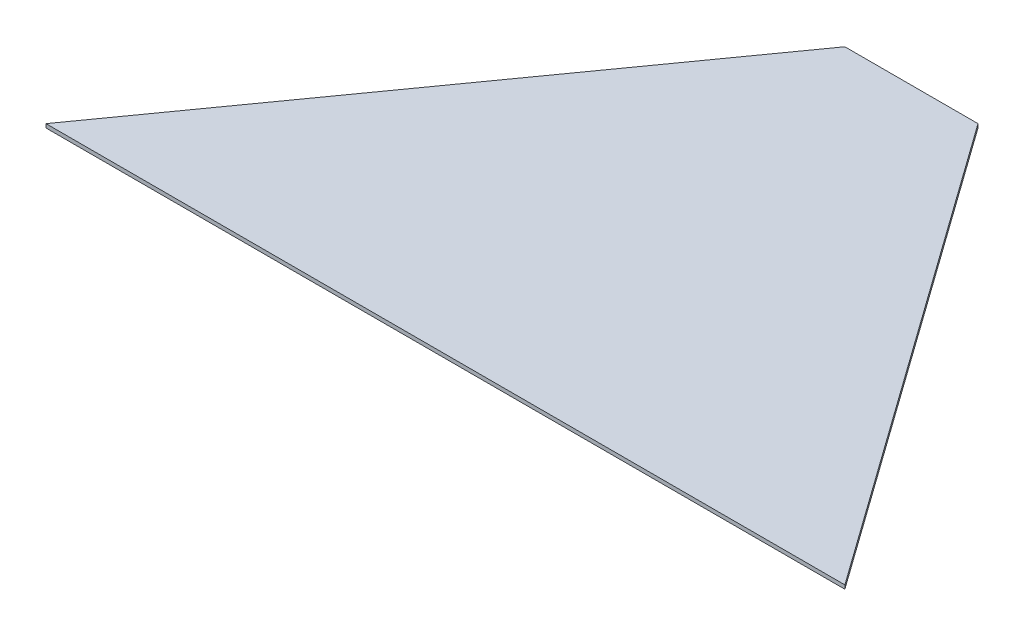
SolidWorks part; units mm, degrees
ref_plane "Front Plane" through (0, 0, 0) normal (0, 0, 1) x (1, 0, 0)
ref_plane "Top Plane" through (0, 0, 0) normal (0, 1, 0) x (1, 0, 0)
ref_plane "Right Plane" through (0, 0, 0) normal (1, 0, 0) x (0, 0, -1)
sketch "Sketch1" plane through (0, 0, 0) normal (0, 1, 0) x (1, 0, 0)
  line L0 (-17.5, 122.5) -> (17.5, 122.5)
  line L1 (17.5, 122.5) -> (105, 0)
  line L2 (105, 0) -> (-105, 0)
  line L3 (-105, 0) -> (-17.5, 122.5)
  point P2 (0, 0)
  dimension "D1" = 122.5
  dimension "D2" = 210
  dimension "D3" = 35
extrude "Boss-Extrude1" add sketch "Sketch1" along normal blind 1
